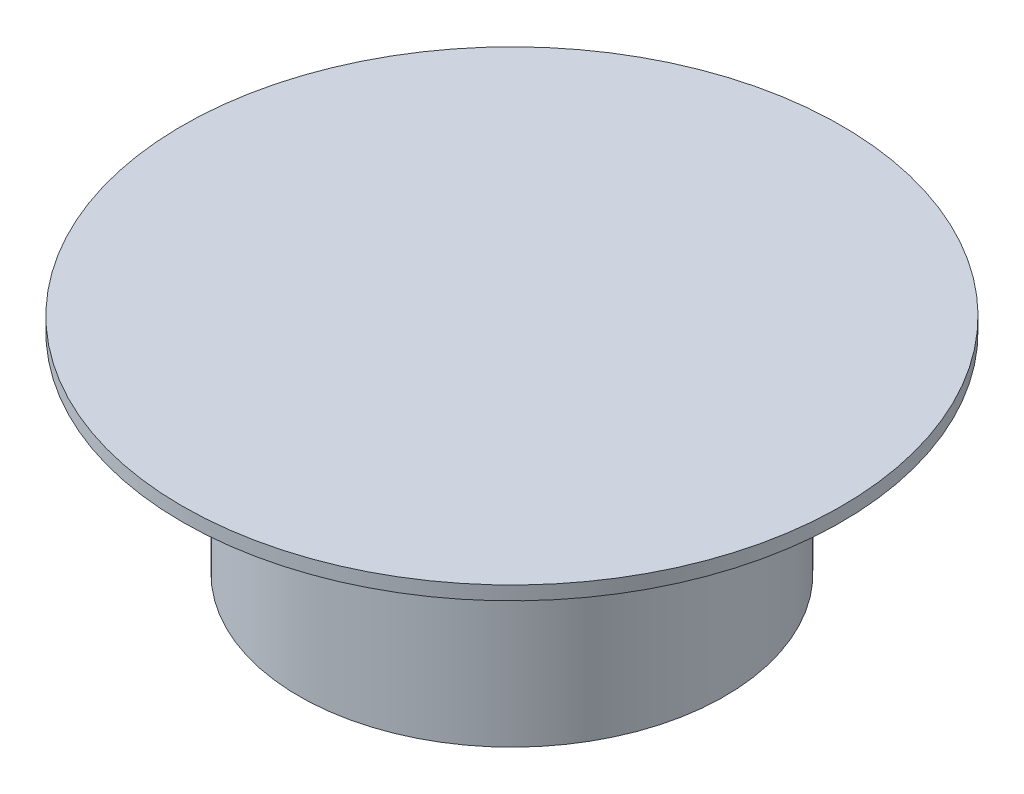
SolidWorks part; units mm, degrees
ref_plane "Front Plane" through (0, 0, 0) normal (0, 0, 1) x (1, 0, 0)
ref_plane "Top Plane" through (0, 0, 0) normal (0, 1, 0) x (1, 0, 0)
ref_plane "Right Plane" through (0, 0, 0) normal (1, 0, 0) x (0, 0, -1)
sketch "Sketch1" plane through (0, 0, 0) normal (0, 1, 0) x (1, 0, 0)
  circle A0 centre (0, 0) radius 3.875
  dimension "D1" = 7.75
extrude "Boss-Extrude1" add sketch "Sketch1" along normal blind 3.81
sketch "Sketch2" plane through (0, 3.81, 0) normal (0, 1, 0) x (1, 0, 0)
  circle A0 centre (0, 0) radius 6
  dimension "D1" = 12
extrude "Boss-Extrude2" add sketch "Sketch2" along normal blind 0.25
